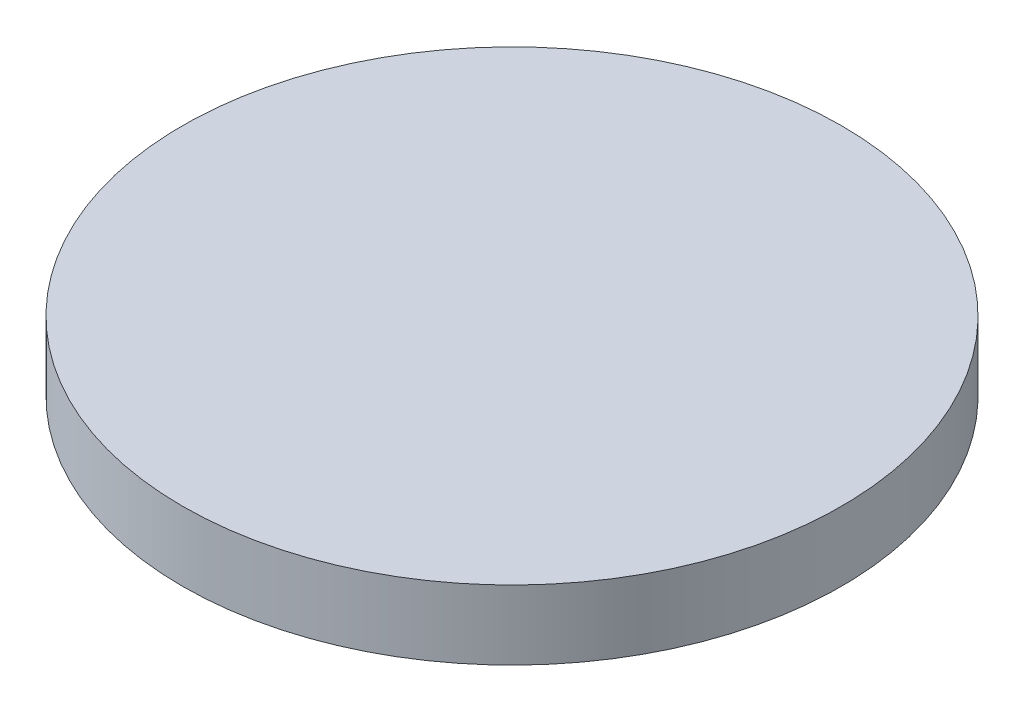
SolidWorks part; units mm, degrees
material "玻璃"
ref_plane "前视基准面" through (0, 0, 0) normal (0, 0, 1) x (1, 0, 0)
ref_plane "上视基准面" through (0, 0, 0) normal (0, 1, 0) x (1, 0, 0)
ref_plane "右视基准面" through (0, 0, 0) normal (1, 0, 0) x (0, 0, -1)
sketch "草图1" plane through (0, 0, 0) normal (0, 1, 0) x (1, 0, 0)
  circle A0 centre (0, 0) radius 57
  dimension "D1" = 114
extrude "D114 主观察窗" add sketch "草图1" along normal blind 12
